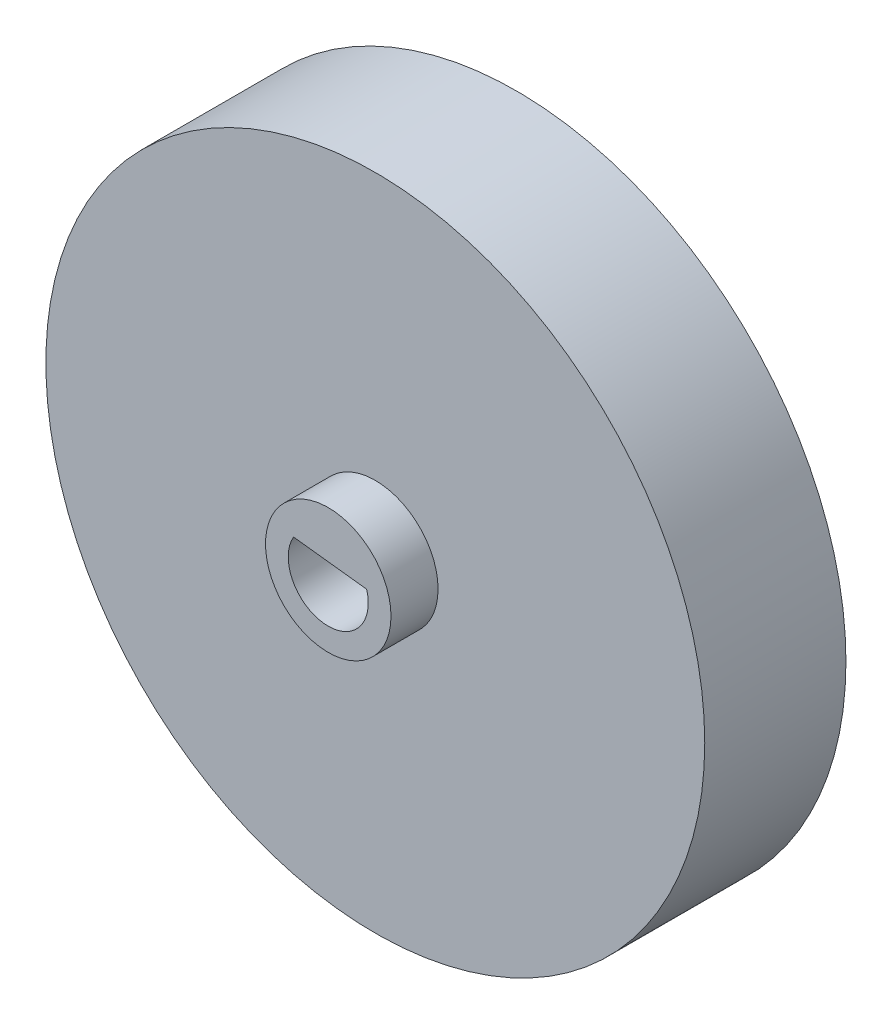
SolidWorks part; units mm, degrees
ref_plane "前视基准面" through (0, 0, 0) normal (0, 0, 1) x (1, 0, 0)
ref_plane "上视基准面" through (0, 0, 0) normal (0, 1, 0) x (1, 0, 0)
ref_plane "右视基准面" through (0, 0, 0) normal (1, 0, 0) x (0, 0, -1)
other "Configuration Table"
sketch "草图1" plane through (0, 0, 0) normal (0, 0, 1) x (1, 0, 0)
  line L0 (4.894, 1.4347) -> (-4.4239, 2.5376)
  circle A0 centre (0, 0) radius 8
  arc A1 (-4.4239, 2.5376) -> (4.894, 1.4347) centre (0, 0) ccw
extrude "凸台-拉伸1" add sketch "草图1" along normal blind 24
sketch "草图2" plane through (0, 0, 0) normal (0, 0, 1) x (1, 0, 0)
  circle A0 centre (0, 0) radius 42
  circle A1 centre (0, 0) radius 8
extrude "凸台-拉伸2" add sketch "草图2" along normal blind 18
sketch "草图3" plane through (0, 0, 0) normal (0, 0, 1) x (1, 0, 0)
  line L0 (37.445, 2.0305) -> (37.5326, 2.0353)
  line L1 (37.5326, 2.0353) -> (37.5954, 2.0363)
  line L2 (37.5954, 2.0363) -> (37.7836, 2.0295)
  line L3 (37.7836, 2.0295) -> (38.0963, 2.0006)
  line L4 (38.0963, 2.0006) -> (38.531, 1.9351)
  line L5 (38.531, 1.9351) -> (39.0842, 1.9351)
  line L6 (39.0842, 1.9351) -> (39.751, 1.9351)
  line L7 (39.751, 1.9351) -> (40.5253, 1.3796)
  line L8 (40.5253, 1.3796) -> (41.4002, 1.3796)
  line L9 (41.9773, 1.3796) -> (42, 0)
  line L10 (42, 0) -> (41.9968, -0.5224)
  line L11 (41.9968, -0.5224) -> (41.987, -1.0447)
  line L12 (41.987, -1.0447) -> (40.5253, -1.0447)
  line L13 (40.5253, -1.0447) -> (39.751, -2.0305)
  line L14 (39.751, -2.0305) -> (39.0842, -2.0305)
  line L15 (39.0842, -2.0305) -> (38.531, -2.0305)
  line L16 (38.531, -2.0305) -> (38.0963, -2.0006)
  line L17 (38.0963, -2.0006) -> (37.7836, -2.0295)
  line L18 (37.7836, -2.0295) -> (37.445, -2.0305)
  line L19 (37.445, -2.0305) -> (37.5326, -2.0353)
  line L20 (37.5326, -2.0353) -> (37.445, -2.0305)
  arc A0 (37.445, -2.0305) -> (37.445, 2.0305) centre (0, 0) ccw
  circle A1 centre (0, 0) radius 42 construction
